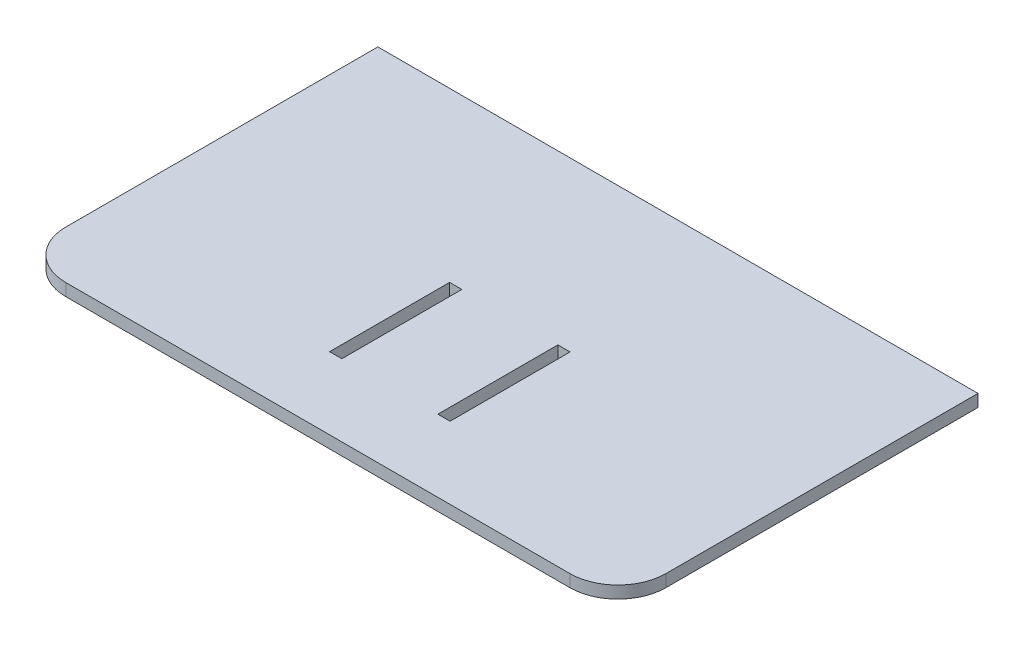
SolidWorks part; units mm, degrees
ref_plane "Front Plane" through (0, 0, 0) normal (0, 0, 1) x (1, 0, 0)
ref_plane "Top Plane" through (0, 0, 0) normal (0, 1, 0) x (1, 0, 0)
ref_plane "Right Plane" through (0, 0, 0) normal (1, 0, 0) x (0, 0, -1)
sketch "Sketch1" plane through (0, 0, 0) normal (0, 1, 0) x (1, 0, 0)
  line L1 (105, -75) -> (-105, -75)
  line L2 (125, -55) -> (125, 75)
  line L3 (125, 75) -> (-125, 75)
  line L4 (-125, -55) -> (-125, 75)
  line L5 (125, -75) -> (-125, 75) construction
  line L6 (125, 75) -> (-125, -75) construction
  line L7 (-20, -45) -> (-25.1, -45)
  line L8 (-20, -45) -> (-20, 5)
  line L9 (-20, 5) -> (-25.1, 5)
  line L10 (-25.1, -45) -> (-25.1, 5)
  line L11 (-20, -45) -> (-25.1, 5) construction
  line L12 (-20, 5) -> (-25.1, -45) construction
  line L13 (25.1, -45) -> (20, -45)
  line L14 (25.1, -45) -> (25.1, 5)
  line L15 (25.1, 5) -> (20, 5)
  line L16 (20, -45) -> (20, 5)
  line L17 (25.1, -45) -> (20, 5) construction
  line L18 (25.1, 5) -> (20, -45) construction
  arc A0 (105, -75) -> (125, -55) centre (105, -55) ccw
  arc A1 (-105, -75) -> (-125, -55) centre (-105, -55) cw
  point P0 (0, 0)
  point P12 (-22.55, -20)
  point P17 (22.55, -20)
  point P22 (0, 0)
  dimension "D3" = 20
  dimension "D1" = 250
  dimension "D2" = 150
  dimension "D4" = 5.1
  dimension "D5" = 5.1
  dimension "D6" = 20
  dimension "D7" = 20
  dimension "D8" = 30
  dimension "D9" = 50
extrude "Boss-Extrude1" add sketch "Sketch1" along normal blind 5.1
